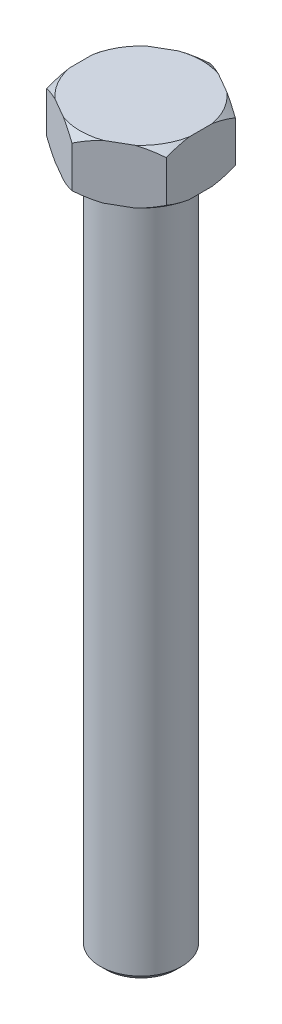
SolidWorks part; units mm, degrees
ref_plane "Front Plane" through (0, 0, 0) normal (0, 0, 1) x (1, 0, 0)
ref_plane "Top Plane" through (0, 0, 0) normal (0, 1, 0) x (1, 0, 0)
ref_plane "Right Plane" through (0, 0, 0) normal (1, 0, 0) x (0, 0, -1)
sketch "Sketch1" plane through (0, 0, 0) normal (0, 1, 0) x (1, 0, 0)
  line L1 (0, 12.7017) -> (-11, 6.3509)
  line L2 (-11, 6.3509) -> (-11, -6.3509)
  line L3 (-11, -6.3509) -> (0, -12.7017)
  line L4 (0, -12.7017) -> (11, -6.3509)
  line L5 (11, -6.3509) -> (11, 6.3509)
  line L6 (11, 6.3509) -> (0, 12.7017)
  circle A0 centre (0, 0) radius 11 construction
  dimension "D1" = 22
extrude "Boss-Extrude1" add sketch "Sketch1" along normal blind 10
sketch "Sketch2" plane through (0, 0, 0) normal (0, -1, 0) x (1, 0, 0)
  circle A0 centre (0, 0) radius 7.5
  dimension "D1" = 15
extrude "Boss-Extrude2" add sketch "Sketch2" along normal blind 126
cosmetic thread "Cosmetic Thread2" parameters "D1"=20, "D2"=11.797
chamfer "Chamfer1" distance 1 angle 45 1 edges at (0, -126, -7.5)
sketch "Sketch4" plane through (0, 0, 0) normal (1, 0, 0) x (0, 0, -1)
  line L0 (0, 0) -> (0, 15.2986) construction
  line L1 (-12.7017, 10) -> (-11.2017, 10)
  line L2 (-12.7017, 10) -> (-6.3509, 10) construction
  line L3 (-11.2017, 10) -> (-12.7017, 8.8)
  line L4 (-12.7017, 10) -> (-12.7017, 0) construction
  line L5 (-12.7017, 8.8) -> (-12.7017, 10)
  line L6 (-12.7017, 0) -> (-11.2017, 0)
  line L7 (-12.7017, 0) -> (-6.3509, 0) construction
  line L8 (-11.2017, 0) -> (-12.7017, 1.2)
  line L9 (-12.7017, 1.2) -> (-12.7017, 0)
  dimension "D1" = 1.5
  dimension "D2" = 1.2
  dimension "D3" = 1.5
  dimension "D4" = 1.2
revolve "Cut-Revolve3" cut sketch "Sketch4" angle 360 about L0
